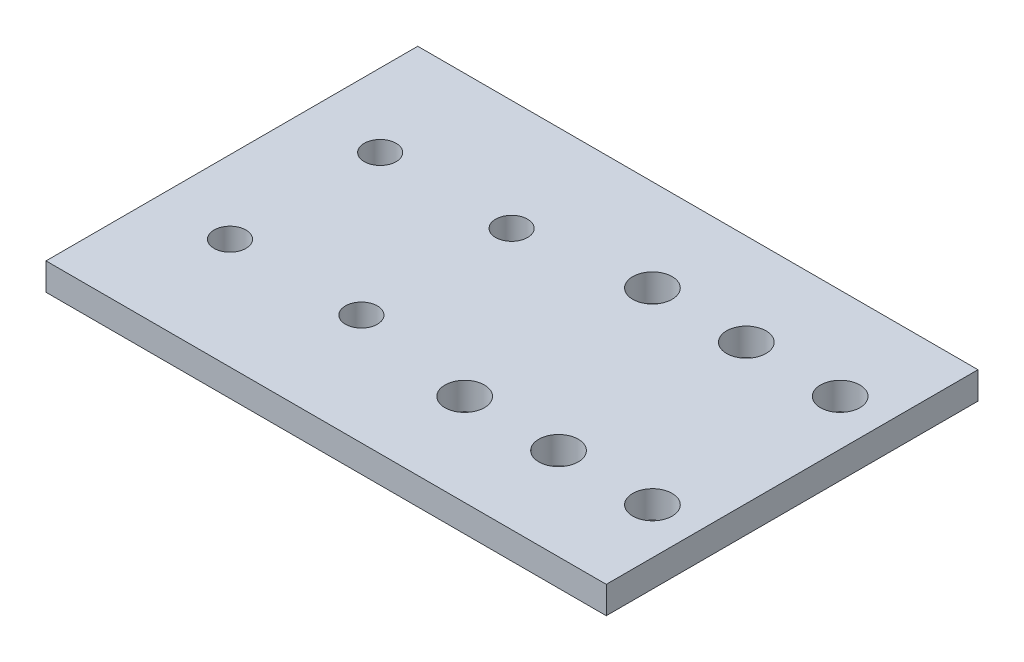
SolidWorks part; units mm, degrees
ref_plane "前视基准面" through (0, 0, 0) normal (0, 0, 1) x (1, 0, 0)
ref_plane "上视基准面" through (0, 0, 0) normal (0, 1, 0) x (1, 0, 0)
ref_plane "右视基准面" through (0, 0, 0) normal (1, 0, 0) x (0, 0, -1)
other "Configuration Table"
sketch "草图1" plane through (0, 0, 0) normal (0, 1, 0) x (1, 0, 0)
  line L0 (0, 120) -> (0, -49880) construction
  line L1 (-100, -120) -> (100, -120)
  line L2 (-100, -120) -> (-100, 120)
  line L3 (-100, 120) -> (100, 120)
  line L4 (100, -120) -> (100, 120)
  line L5 (-100, -120) -> (100, 120) construction
  line L6 (-100, 120) -> (100, -120) construction
  line L7 (-100, 120) -> (-70, 120)
  line L8 (-100, 120) -> (-100, 80)
  line L9 (-100, 80) -> (-70, 80)
  line L10 (-70, 120) -> (-70, 80)
  line L11 (-65, 0) -> (49935, 0) construction
  line L12 (-70, 120) -> (-70, 113)
  line L13 (-70, 113) -> (-70, 87)
  line L14 (-70, 87) -> (-70, 80)
  line L15 (-70, 113) -> (-40, 113)
  line L16 (-40, 113) -> (-40, 87)
  line L17 (-40, 87) -> (-70, 87)
  line L18 (-70, 113) -> (-70, 108)
  line L19 (-70, 87) -> (-70, 92)
  line L20 (-40, 87) -> (-48, 87)
  line L21 (-48, 87) -> (-48, 92)
  line L22 (-48, 92) -> (-40, 92)
  line L23 (-70, 92) -> (-62, 92)
  line L24 (-62, 92) -> (-62, 87)
  line L25 (-70, 100) -> (-40, 100) construction
  line L26 (0, 120) -> (0, 0)
  line L27 (0, 0) -> (-100, 0)
  line L28 (-70, 80) -> (0, 80)
  line L29 (100, 80) -> (70, 80)
  line L30 (70, 120) -> (70, 80)
  line L31 (100, -80) -> (70, -80)
  line L32 (70, -120) -> (70, -80)
  line L33 (-70, -120) -> (-70, -80)
  line L34 (-100, -80) -> (-70, -80)
  line L35 (0, 120) -> (0, 100)
  line L36 (0, 100) -> (-25, 100)
  line L37 (-25, 100) -> (-25, 115)
  line L38 (-25, 100) -> (-25, 85)
  line L39 (-25, 85) -> (-5, 85)
  line L40 (-25, 115) -> (-5, 115)
  line L41 (-5, 115) -> (-5, 85)
  line L42 (5, 115) -> (5, 85)
  line L43 (25, 100) -> (25, 85)
  line L44 (25, 85) -> (5, 85)
  line L45 (25, 115) -> (5, 115)
  line L46 (25, 100) -> (25, 115)
  line L47 (25, -85) -> (5, -85)
  line L48 (25, -100) -> (25, -85)
  line L49 (25, -100) -> (25, -115)
  line L50 (25, -115) -> (5, -115)
  line L51 (5, -115) -> (5, -85)
  line L52 (-25, -100) -> (-25, -115)
  line L53 (-25, -100) -> (-25, -85)
  line L54 (-25, -85) -> (-5, -85)
  line L55 (-5, -115) -> (-5, -85)
  line L56 (-25, -115) -> (-5, -115)
  line L57 (-100, 0) -> (-90, 0)
  line L58 (0, 120) -> (0, 100)
  line L59 (0, 120) -> (0, 110)
  line L60 (-70, 80) -> (0, 80)
  line L61 (-70, 113) -> (-20, 113)
  line L62 (-70, 80) -> (0, 80)
  line L63 (-20, 113) -> (-40, 113)
  line L64 (-20, 113) -> (-20, 87)
  line L65 (-20, 87) -> (-40, 87)
  line L66 (-40, 113) -> (-40, 87)
  line L67 (-20, 87) -> (-20, 80)
  line L68 (-20, 80) -> (-20, 120)
  circle A0 centre (-62, 92) radius 1.7
  circle A1 centre (-48, 92) radius 1.7
  circle A2 centre (-48, 108) radius 1.7
  circle A3 centre (-62, 108) radius 1.7
  circle A4 centre (48, 108) radius 1.7
  circle A5 centre (48, 92) radius 1.7
  circle A6 centre (62, 92) radius 1.7
  circle A7 centre (62, 108) radius 1.7
  circle A8 centre (62, -108) radius 1.7
  circle A9 centre (62, -92) radius 1.7
  circle A10 centre (48, -92) radius 1.7
  circle A11 centre (48, -108) radius 1.7
  circle A12 centre (-48, -92) radius 1.7
  circle A13 centre (-62, -92) radius 1.7
  circle A14 centre (-48, -108) radius 1.7
  circle A15 centre (-62, -108) radius 1.7
  circle A16 centre (-90, 0) radius 2.5
  circle A17 centre (-90, 50) radius 2.5
  circle A18 centre (-90, -50) radius 2.5
  circle A19 centre (90, -50) radius 2.5
  circle A20 centre (90, 0) radius 2.5
  circle A21 centre (90, 50) radius 2.5
  circle A22 centre (0, 110) radius 2.5
  circle A23 centre (35, 110) radius 2.5
  point P0 (0, 0)
  point P11 (0, 120)
  point P14 (-100, 0)
  point P15 (100, 0)
  dimension "D12" = 3.4
  dimension "D13" = 3.4
  dimension "D19" = 5
  dimension "D23" = 5
  dimension "D1" = 200
  dimension "D2" = 240
  dimension "D3" = 30
  dimension "D4" = 40
  dimension "D5" = 7
  dimension "D6" = 7
  dimension "D7" = 30
  dimension "D8" = 5
  dimension "D9" = 5
  dimension "D10" = 8
  dimension "D11" = 8
  dimension "D14" = 25
  dimension "D15" = 15
  dimension "D16" = 15
  dimension "D17" = 20
  dimension "D18" = 10
  dimension "D21" = 20
  dimension "D22" = 10
  dimension "D25" = 50
  dimension "D26" = 40
  dimension "D20" = 2
  dimension "D24" = 2
extrude "凸台-拉伸3" add sketch "草图1" along normal blind 2.9 contours A1 L22 L16 L15 L10 L13 L23 A0 L24 L17 L21 A2 A3 | A0 L23 L10 L17 L24 | A1 L21 L17 L16 L22 | L67 L39 L38 L65 L17 L10 L28 | L65 L38 L37 L61 L16 | L65 L64 L36 L38 | L64 L61 L37 L36 | L67 L65 L38 L39 | L40 L68 L3 L10 L15 L61 L37 | L61 L68 L40 L37
sketch "草图3" plane through (0, 2.9, 0) normal (0, 1, 0) x (1, 0, 0)
  line L0 (-1070, 100) -> (48930, 100)
  line L1 (-70, 120) -> (-70, 80) construction
  line L2 (-20, 100) -> (-20, 110)
  line L3 (-20, 120) -> (-20, 80) construction
  line L4 (-20, 110) -> (-25, 110)
  circle A0 centre (-25, 110) radius 2.1
  circle A1 centre (-25, 90) radius 2.1
  circle A2 centre (-35, 90) radius 2.1
  circle A3 centre (-35, 110) radius 2.1
  point P5 (-70, 100)
  dimension "D3" = 4.2
  dimension "D1" = 10
  dimension "D2" = 5
  dimension "D4" = 2
extrude "切除-拉伸3" cut sketch "草图3" against normal blind 2.9
sketch "草图4" plane through (0, 2.9, 0) normal (0, 1, 0) x (1, 0, 0)
  line L0 (-25, 110) -> (-15, 110)
  line L1 (-20, 120) -> (0, 120)
  line L2 (-20, 120) -> (-20, 80)
  line L3 (-20, 80) -> (0, 80)
  line L4 (0, 120) -> (0, 80)
  line L5 (-1020, 100) -> (48980, 100)
  circle A0 centre (-15, 110) radius 2.1
  circle A2 centre (-15, 90) radius 2.1
  circle A3 centre (-5, 110) radius 2.1
  circle A4 centre (-5, 90) radius 2.1
  point P12 (-20, 100)
  dimension "D3" = 4.2
  dimension "D1" = 20
  dimension "D2" = 10
  dimension "D4" = 2
extrude "凸台-拉伸4" add sketch "草图4" against normal blind 2.9
sketch "草图5" plane through (0, 2.9, 0) normal (0, 1, 0) x (1, 0, 0)
  line L0 (-69.8, 119.8) -> (-69.8, 80.2)
  line L1 (-70, 120) -> (0, 120)
  line L2 (-70, 120) -> (-70, 80)
  line L3 (-70, 80) -> (0, 80)
  line L4 (0, 120) -> (0, 80)
  line L5 (-69.8, 80.2) -> (-0.2, 80.2)
  line L6 (-0.2, 119.8) -> (-0.2, 80.2)
  line L7 (-69.8, 119.8) -> (-0.2, 119.8)
  dimension "D1" = 0.2
extrude "切除-拉伸4" cut sketch "草图5" against normal blind 2.9
sketch "草图6" plane through (0, 2.9, 0) normal (0, 1, 0) x (1, 0, 0)
  line L0 (-20.0349, 119.8) -> (-20.0349, 80.2)
  line L1 (-0.2, 119.8) -> (-69.8, 119.8) construction
  line L2 (-69.8, 80.2) -> (-0.2, 80.2) construction
  line L3 (-20.0349, 80.2) -> (-0.2, 80.2)
  line L4 (-0.2, 80.2) -> (-0.2, 119.8)
  line L5 (-0.2, 119.8) -> (-20.0349, 119.8)
  line L6 (-10.1174, 119.8) -> (-10.1174, 80.2)
  circle M1 centre (-5, 110) radius 2.1
  circle M3 centre (-5, 90) radius 2.1
  line M13 (-0.2, 80.2) -> (-0.2, 119.8)
  line M14 (-0.2, 119.8) -> (-69.8, 119.8)
extrude "切除-拉伸5" cut sketch "草图6" against normal blind 10 contours L6 L3 M14 M13 M3 M1
